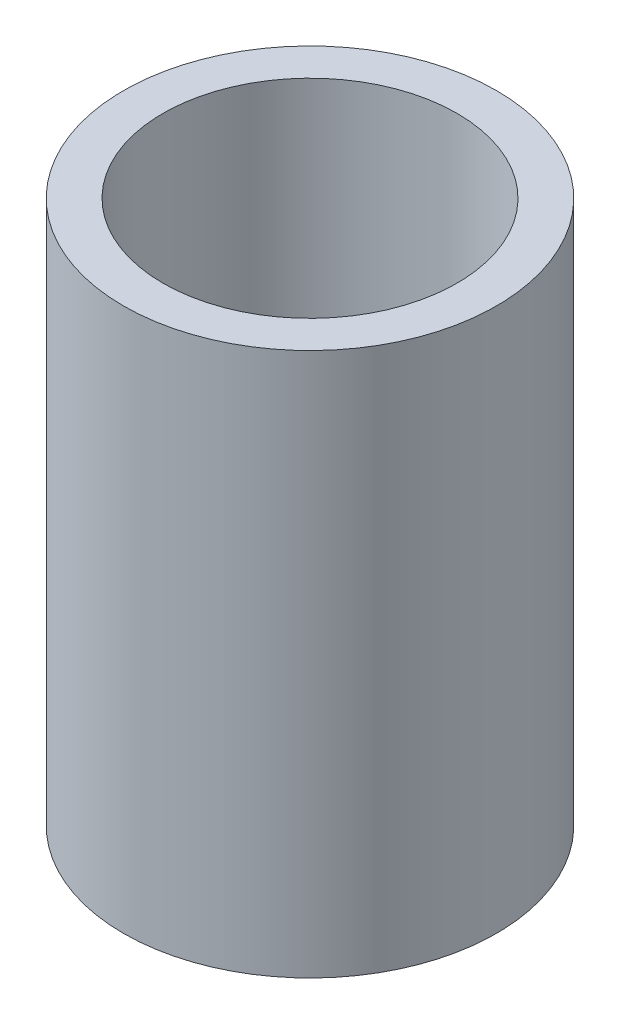
SolidWorks part; units mm, degrees
material "6061 Alloy"
ref_plane "Front Plane" through (0, 0, 0) normal (0, 0, 1) x (1, 0, 0)
ref_plane "Top Plane" through (0, 0, 0) normal (0, 1, 0) x (1, 0, 0)
ref_plane "Right Plane" through (0, 0, 0) normal (1, 0, 0) x (0, 0, -1)
sketch "Sketch1" plane through (0, 0, 0) normal (0, 1, 0) x (1, 0, 0)
  circle A0 centre (0, 0) radius 5.0075
  circle A1 centre (0, 0) radius 6.35
  dimension "D1" = 12.7
  dimension "D2" = 10.015
extrude "Boss-Extrude1" add sketch "Sketch1" along normal blind 18.5
